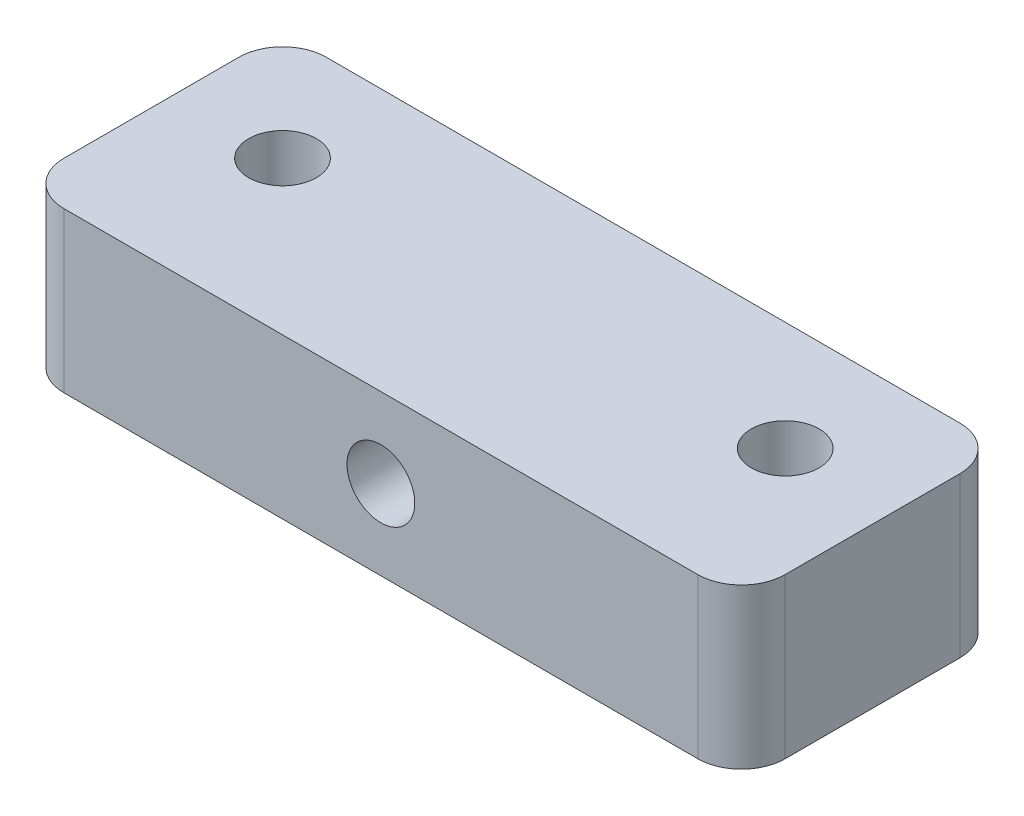
SolidWorks part; units mm, degrees
material "ABS"
ref_plane "Front" through (0, 0, 0) normal (0, 0, 1) x (1, 0, 0)
ref_plane "Top" through (0, 0, 0) normal (0, 1, 0) x (1, 0, 0)
ref_plane "Right" through (0, 0, 0) normal (1, 0, 0) x (0, 0, -1)
sketch "Esquisse1" plane through (0, 0, 0) normal (0, 1, 0) x (1, 0, 0)
  line L0 (0, -50) -> (0, 50) construction
  line L1 (-16.5, 12) -> (16.5, 12)
  line L2 (-16.5, 12) -> (-16.5, 0)
  line L3 (-16.5, 0) -> (16.5, 0)
  line L4 (16.5, 12) -> (16.5, 0)
  circle A0 centre (-11.5, 7) radius 1.55
  circle A2 centre (11.5, 7) radius 1.55
  dimension "D1" = 23
  dimension "D2" = 3.1
  dimension "D3" = 7
  dimension "D4" = 5
  dimension "D5" = 5
extrude "Boss.-Extru.1" add sketch "Esquisse1" along normal mid plane 7.3
sketch "Esquisse4" plane through (0, 0, 0) normal (1, 0, 0) x (0, 0, -1)
  line L0 (0, 0) -> (12, 0)
  line L1 (12, 3.65) -> (12, -3.65) construction
  line L2 (12, 0) -> (12, 2.3374)
  line L3 (12, 2.3374) -> (7, 1.9)
  line L4 (7, 1.9) -> (3, 1.9)
  line L5 (3, 1.9) -> (3, 1.55)
  line L6 (3, 1.55) -> (0, 1.55)
  line L7 (0, 3.65) -> (0, -3.65) construction
  line L8 (0, 1.55) -> (0, 0)
  line L9 (-12, 0) -> (0, 0) construction
  dimension "D1" = 3.1
  dimension "D2" = 3.8
  dimension "D3" = 3
  dimension "D4" = 4
  dimension "D5" = 5
revolve "Enlèvement de matière-Révolution1" cut sketch "Esquisse4" angle 360 about L9
sketch "Esquisse5" plane through (0, 3.65, 0) normal (0, 1, 0) x (1, 0, 0)
  circle A0 centre (-11.5, 7) radius 1.9
  circle A1 centre (11.5, 7) radius 1.9
  dimension "D1" = 3.8
extrude "Enlèv. mat.-Extru.3" cut sketch "Esquisse5" against normal through all from offset 3 offset against normal yes
fillet "Congé1" radius 2 4 edges at (-16.5, 0, -12) (16.5, 0, -12) (16.5, 0, 0) (-16.5, 0, 0)
